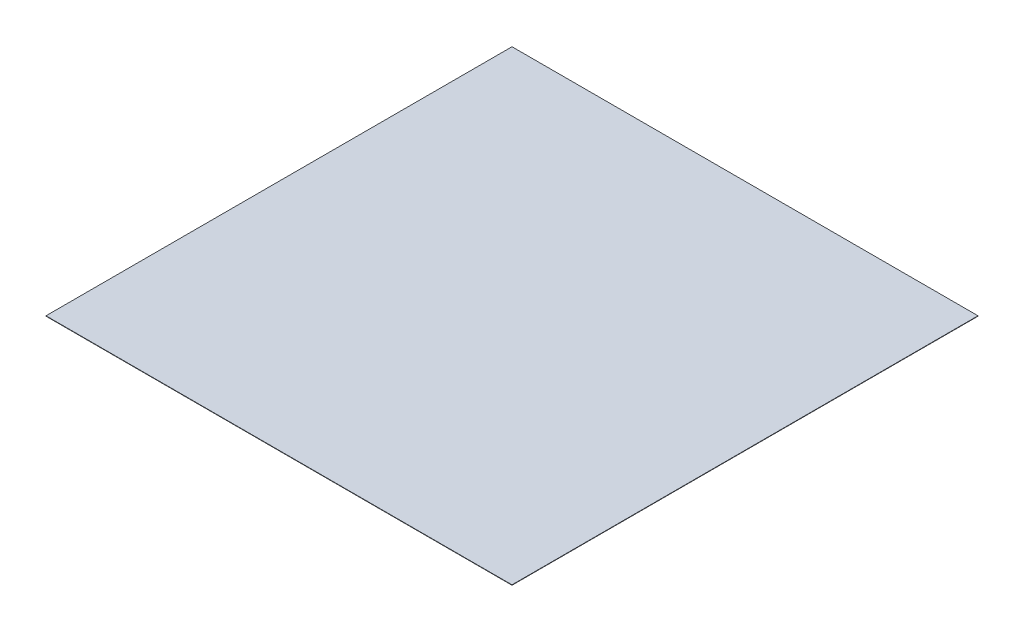
SolidWorks part; units mm, degrees
ref_plane "Front Plane" through (0, 0, 0) normal (0, 0, 1) x (1, 0, 0)
ref_plane "Top Plane" through (0, 0, 0) normal (0, 1, 0) x (1, 0, 0)
ref_plane "Right Plane" through (0, 0, 0) normal (1, 0, 0) x (0, 0, -1)
ref_plane "Plane1" through (0, 0, 134.8832) normal (0, 0, -1) x (-1, 0, 0)
sketch "Sketch2" plane through (0, 0, 134.8832) normal (0, 0, -1) x (-1, 0, 0)
  line L0 (-16.0101, 154.0644) -> (-16.0101, 120.0644)
  line L1 (-16.0101, 154.0644) -> (-16.0101, 120.0644) construction
  line L2 (-23.0101, 117.0644) -> (-19.0101, 117.0644)
  line L3 (-23.0101, 117.0644) -> (-19.0101, 117.0644) construction
  line L4 (-26.0101, 110.0644) -> (-26.0101, 114.0644)
  line L5 (-26.0101, 110.0644) -> (-26.0101, 114.0644) construction
  line L6 (-29.0101, 107.0644) -> (-63.0101, 107.0644)
  line L7 (-29.0101, 107.0644) -> (-63.0101, 107.0644) construction
  line L8 (-76.0101, 120.0644) -> (-76.0101, 154.0644)
  line L9 (-76.0101, 120.0644) -> (-76.0101, 154.0644) construction
  line L10 (-73.0101, 117.0644) -> (-69.0101, 117.0644)
  line L11 (-73.0101, 117.0644) -> (-69.0101, 117.0644) construction
  line L12 (-66.0101, 114.0644) -> (-66.0101, 110.0644)
  line L13 (-66.0101, 114.0644) -> (-66.0101, 110.0644) construction
  line L14 (-63.0101, 167.0644) -> (-29.0101, 167.0644)
  line L15 (-63.0101, 167.0644) -> (-29.0101, 167.0644) construction
  line L16 (-26.0101, 160.0644) -> (-26.0101, 164.0644)
  line L17 (-26.0101, 160.0644) -> (-26.0101, 164.0644) construction
  line L18 (-19.0101, 157.0644) -> (-23.0101, 157.0644)
  line L19 (-19.0101, 157.0644) -> (-23.0101, 157.0644) construction
  line L20 (-69.0101, 157.0644) -> (-73.0101, 157.0644)
  line L21 (-69.0101, 157.0644) -> (-73.0101, 157.0644) construction
  line L22 (-66.0101, 164.0644) -> (-66.0101, 160.0644)
  line L23 (-66.0101, 164.0644) -> (-66.0101, 160.0644) construction
  line L24 (-66.5101, 164.0644) -> (-66.5101, 160.0644)
  line L25 (-69.0101, 157.5644) -> (-73.0101, 157.5644)
  line L26 (-76.5101, 120.0644) -> (-76.5101, 154.0644)
  line L27 (-73.0101, 116.5644) -> (-69.0101, 116.5644)
  line L28 (-66.5101, 114.0644) -> (-66.5101, 110.0644)
  line L29 (-29.0101, 106.5644) -> (-63.0101, 106.5644)
  line L30 (-25.5101, 110.0644) -> (-25.5101, 114.0644)
  line L31 (-23.0101, 116.5644) -> (-19.0101, 116.5644)
  line L32 (-15.5101, 154.0644) -> (-15.5101, 120.0644)
  line L33 (-19.0101, 157.5644) -> (-23.0101, 157.5644)
  line L34 (-25.5101, 160.0644) -> (-25.5101, 164.0644)
  line L36 (-29.0101, 167.0644) -> (-84.0101, 167.0644)
  line L37 (-29.0101, 167.0644) -> (-8.0101, 167.0644)
  line L38 (-84.0101, 120.0644) -> (-84.0101, 154.0644)
  line L39 (-73.9683, 109.1063) -> (-73.9683, 109.1063)
  line L40 (-73.9683, 109.1063) -> (-73.9683, 109.1063)
  line L41 (-29.0101, 99.0644) -> (-63.0101, 99.0644)
  line L42 (-18.0519, 109.1063) -> (-18.0519, 109.1063)
  line L43 (-18.0519, 109.1063) -> (-18.0519, 109.1063)
  line L44 (-8.0101, 154.0644) -> (-8.0101, 120.0644)
  line L48 (-8.0101, 154.0644) -> (-8.0101, 167.0644)
  line L50 (-84.0101, 154.0644) -> (-84.0101, 167.0644)
  line L53 (-18.0519, 165.0226) -> (-18.0519, 165.0226) construction
  line L54 (-18.0519, 165.0226) -> (-18.0519, 165.0226) construction
  line L55 (-73.9683, 165.0226) -> (-73.9683, 165.0226) construction
  line L56 (-73.9683, 165.0226) -> (-73.9683, 165.0226) construction
  line L57 (-63.0101, 167.5644) -> (-29.0101, 167.5644) construction
  line L58 (-63.0101, 175.0644) -> (-29.0101, 175.0644) construction
  arc A0 (-19.0101, 117.0644) -> (-16.0101, 120.0644) centre (-19.0101, 120.0644) ccw
  arc A1 (-19.0101, 117.0644) -> (-16.0101, 120.0644) centre (-19.0101, 120.0644) ccw construction
  arc A2 (-23.0101, 117.0644) -> (-26.0101, 114.0644) centre (-23.0101, 114.0644) ccw
  arc A3 (-23.0101, 117.0644) -> (-26.0101, 114.0644) centre (-23.0101, 114.0644) ccw construction
  arc A4 (-29.0101, 107.0644) -> (-26.0101, 110.0644) centre (-29.0101, 110.0644) ccw
  arc A5 (-29.0101, 107.0644) -> (-26.0101, 110.0644) centre (-29.0101, 110.0644) ccw construction
  arc A6 (-66.0101, 110.0644) -> (-63.0101, 107.0644) centre (-63.0101, 110.0644) ccw
  arc A7 (-66.0101, 110.0644) -> (-63.0101, 107.0644) centre (-63.0101, 110.0644) ccw construction
  arc A8 (-76.0101, 120.0644) -> (-73.0101, 117.0644) centre (-73.0101, 120.0644) ccw
  arc A9 (-76.0101, 120.0644) -> (-73.0101, 117.0644) centre (-73.0101, 120.0644) ccw construction
  arc A10 (-66.0101, 114.0644) -> (-69.0101, 117.0644) centre (-69.0101, 114.0644) ccw
  arc A11 (-66.0101, 114.0644) -> (-69.0101, 117.0644) centre (-69.0101, 114.0644) ccw construction
  arc A12 (-26.0101, 164.0644) -> (-29.0101, 167.0644) centre (-29.0101, 164.0644) ccw
  arc A13 (-26.0101, 164.0644) -> (-29.0101, 167.0644) centre (-29.0101, 164.0644) ccw construction
  arc A14 (-26.0101, 160.0644) -> (-23.0101, 157.0644) centre (-23.0101, 160.0644) ccw
  arc A15 (-26.0101, 160.0644) -> (-23.0101, 157.0644) centre (-23.0101, 160.0644) ccw construction
  arc A16 (-16.0101, 154.0644) -> (-19.0101, 157.0644) centre (-19.0101, 154.0644) ccw
  arc A17 (-16.0101, 154.0644) -> (-19.0101, 157.0644) centre (-19.0101, 154.0644) ccw construction
  arc A18 (-63.0101, 167.0644) -> (-66.0101, 164.0644) centre (-63.0101, 164.0644) ccw
  arc A19 (-63.0101, 167.0644) -> (-66.0101, 164.0644) centre (-63.0101, 164.0644) ccw construction
  arc A20 (-69.0101, 157.0644) -> (-66.0101, 160.0644) centre (-69.0101, 160.0644) ccw
  arc A21 (-69.0101, 157.0644) -> (-66.0101, 160.0644) centre (-69.0101, 160.0644) ccw construction
  arc A22 (-73.0101, 157.0644) -> (-76.0101, 154.0644) centre (-73.0101, 154.0644) ccw
  arc A23 (-73.0101, 157.0644) -> (-76.0101, 154.0644) centre (-73.0101, 154.0644) ccw construction
  arc A24 (-69.0101, 157.5644) -> (-66.5101, 160.0644) centre (-69.0101, 160.0644) ccw
  arc A25 (-73.0101, 157.5644) -> (-76.5101, 154.0644) centre (-73.0101, 154.0644) ccw
  arc A26 (-76.5101, 120.0644) -> (-73.0101, 116.5644) centre (-73.0101, 120.0644) ccw
  arc A27 (-66.5101, 114.0644) -> (-69.0101, 116.5644) centre (-69.0101, 114.0644) ccw
  arc A28 (-66.5101, 110.0644) -> (-63.0101, 106.5644) centre (-63.0101, 110.0644) ccw
  arc A29 (-29.0101, 106.5644) -> (-25.5101, 110.0644) centre (-29.0101, 110.0644) ccw
  arc A30 (-23.0101, 116.5644) -> (-25.5101, 114.0644) centre (-23.0101, 114.0644) ccw
  arc A31 (-19.0101, 116.5644) -> (-15.5101, 120.0644) centre (-19.0101, 120.0644) ccw
  arc A32 (-15.5101, 154.0644) -> (-19.0101, 157.5644) centre (-19.0101, 154.0644) ccw
  arc A33 (-25.5101, 160.0644) -> (-23.0101, 157.5644) centre (-23.0101, 160.0644) ccw
  arc A34 (-25.5101, 164.0644) -> (-27.2073, 167.0644) centre (-29.0101, 164.0644) ccw
  arc A35 (-64.8129, 167.0644) -> (-66.5101, 164.0644) centre (-63.0101, 164.0644) ccw
  arc A37 (-63.0101, 167.5644) -> (-66.5101, 164.0644) centre (-63.0101, 164.0644) ccw construction
  arc A38 (-84.0101, 120.0644) -> (-73.9683, 109.1063) centre (-73.0101, 120.0644) ccw
  arc A39 (-73.9683, 109.1063) -> (-73.9683, 109.1063) centre (-73.9683, 109.1063) ccw
  arc A40 (-73.9683, 109.1063) -> (-63.0101, 99.0644) centre (-63.0101, 110.0644) ccw
  arc A41 (-29.0101, 99.0644) -> (-18.0519, 109.1063) centre (-29.0101, 110.0644) ccw
  arc A42 (-18.0519, 109.1063) -> (-18.0519, 109.1063) centre (-18.0519, 109.1063) ccw
  arc A43 (-18.0519, 109.1063) -> (-8.0101, 120.0644) centre (-19.0101, 120.0644) ccw
  arc A44 (-25.5101, 164.0644) -> (-29.0101, 167.5644) centre (-29.0101, 164.0644) ccw construction
  arc A49 (-8.0101, 154.0644) -> (-18.0519, 165.0226) centre (-19.0101, 154.0644) ccw construction
  arc A50 (-18.0519, 165.0226) -> (-29.0101, 175.0644) centre (-29.0101, 164.0644) ccw construction
  arc A51 (-63.0101, 175.0644) -> (-73.9683, 165.0226) centre (-63.0101, 164.0644) ccw construction
  arc A52 (-73.9683, 165.0226) -> (-84.0101, 154.0644) centre (-73.0101, 154.0644) ccw construction
  arc A53 (-18.0519, 165.0226) -> (-18.0519, 165.0226) centre (-18.0519, 165.0226) ccw construction
  arc A54 (-73.9683, 165.0226) -> (-73.9683, 165.0226) centre (-73.9683, 165.0226) ccw construction
  dimension "D1" = 0.5
  dimension "D2" = 8
extrude "Boss-Extrude1" add sketch "Sketch2" along normal blind 20 contours A41 A43 L44 L48 L37 A34 L34 A33 L33 A32 L32 A31 L31 A30 L30 A29 L29 A28 L28 A27 L27 A26 L26 A25 L25 A24 L24 A35 L36 L50 L38 A38 A40 L41
ref_plane "Plane2" through (0, 167.0644, 0) normal (0, 1, 0) x (1, 0, 0)
sketch "Sketch3" plane through (0, 167.0644, 0) normal (0, 1, 0) x (1, 0, 0)
  line L1 (-1.9899, -144.8832) -> (24.2073, -144.8832)
  line L2 (-1.9899, -144.8832) -> (-1.9899, -104.8832)
  line L3 (-1.9899, -104.8832) -> (24.2073, -104.8832)
  line L4 (98.0101, -144.8832) -> (98.0101, -104.8832)
  line L5 (67.8129, -104.8832) -> (67.8129, -144.8832)
  line L7 (24.2073, -104.8832) -> (24.2073, -144.8832)
  line L9 (48.0101, -104.8832) -> (48.0101, -144.8832) construction
  line L10 (98.0101, -124.8832) -> (-1.9899, -124.8832) construction
  line L13 (67.8129, -104.8832) -> (98.0101, -104.8832)
  line L14 (67.8129, -144.8832) -> (98.0101, -144.8832)
  circle A0 centre (93.0101, -109.8832) radius 1.5
  circle A1 centre (93.0101, -139.8832) radius 1.5
  circle A2 centre (3.0101, -139.8832) radius 1.5
  circle A3 centre (3.0101, -109.8832) radius 1.5
  dimension "D5" = 67.8129
  dimension "D1" = 3
  dimension "D2" = 3.0101
  dimension "D3" = 24.2073
  dimension "D4" = 48.0101
  dimension "D6" = 93.0101
  dimension "D7" = 98.0101
  dimension "D8" = 1.9899
  dimension "D9" = 104.8832
  dimension "D10" = 109.8832
  dimension "D11" = 124.8832
  dimension "D12" = 139.8832
extrude "Boss-Extrude2" add sketch "Sketch3" along normal blind 5 from offset 5 offset against normal yes
ref_plane "Plane3" through (0, 237.0644, 0) normal (0, 1, 0) x (1, 0, 0)
sketch "Sketch4" plane through (0, 237.0644, 0) normal (0, 1, 0) x (1, 0, 0)
  line L0 (0, 0) -> (0, 600) construction
  line L1 (600, 600) -> (-600, 600)
  line L2 (600, 600) -> (600, -600)
  line L3 (600, -600) -> (-600, -600)
  line L4 (-600, 600) -> (-600, -600)
  line L5 (0, 0) -> (600, 0) construction
  dimension "D1" = 1200
  dimension "D2" = 1200
  dimension "D3" = 600
  dimension "D4" = 600
extrude "Boss-Extrude3" add sketch "Sketch4" along normal blind 1 separate body
sketch "Sketch5" plane through (0, 167.0644, 0) normal (0, 1, 0) x (1, 0, 0)
  line L0 (98.0101, -144.8832) -> (98.0101, -104.8832) construction
  line L1 (98.0101, -104.8832) -> (67.8129, -104.8832) construction
  line L2 (67.8129, -144.8832) -> (98.0101, -144.8832) construction
  line L3 (-1.9899, -144.8832) -> (24.2073, -144.8832) construction
  line L4 (-1.9899, -104.8832) -> (-1.9899, -144.8832) construction
  line L5 (24.2073, -104.8832) -> (-1.9899, -104.8832) construction
  line L6 (98.0101, -144.8832) -> (98.0101, -104.8832)
  line L7 (98.0101, -104.8832) -> (67.8129, -104.8832)
  line L8 (67.8129, -144.8832) -> (98.0101, -144.8832)
  line L9 (-1.9899, -144.8832) -> (24.2073, -144.8832)
  line L10 (-1.9899, -104.8832) -> (-1.9899, -144.8832)
  line L11 (24.2073, -104.8832) -> (-1.9899, -104.8832)
  line L12 (24.2073, -104.8832) -> (67.8129, -104.8832)
  line L13 (24.2073, -144.8832) -> (67.8129, -144.8832)
  circle A0 centre (93.0101, -139.8832) radius 1.5 construction
  circle A1 centre (93.0101, -109.8832) radius 1.5 construction
  circle A2 centre (3.0101, -139.8832) radius 1.5 construction
  circle A3 centre (3.0101, -109.8832) radius 1.5 construction
  circle A4 centre (93.0101, -139.8832) radius 1.5
  circle A5 centre (93.0101, -109.8832) radius 1.5
  circle A6 centre (3.0101, -139.8832) radius 1.5
  circle A7 centre (3.0101, -109.8832) radius 1.5
extrude "Boss-Extrude4" add sketch "Sketch5" along normal up to surface (13.5 mm away)
